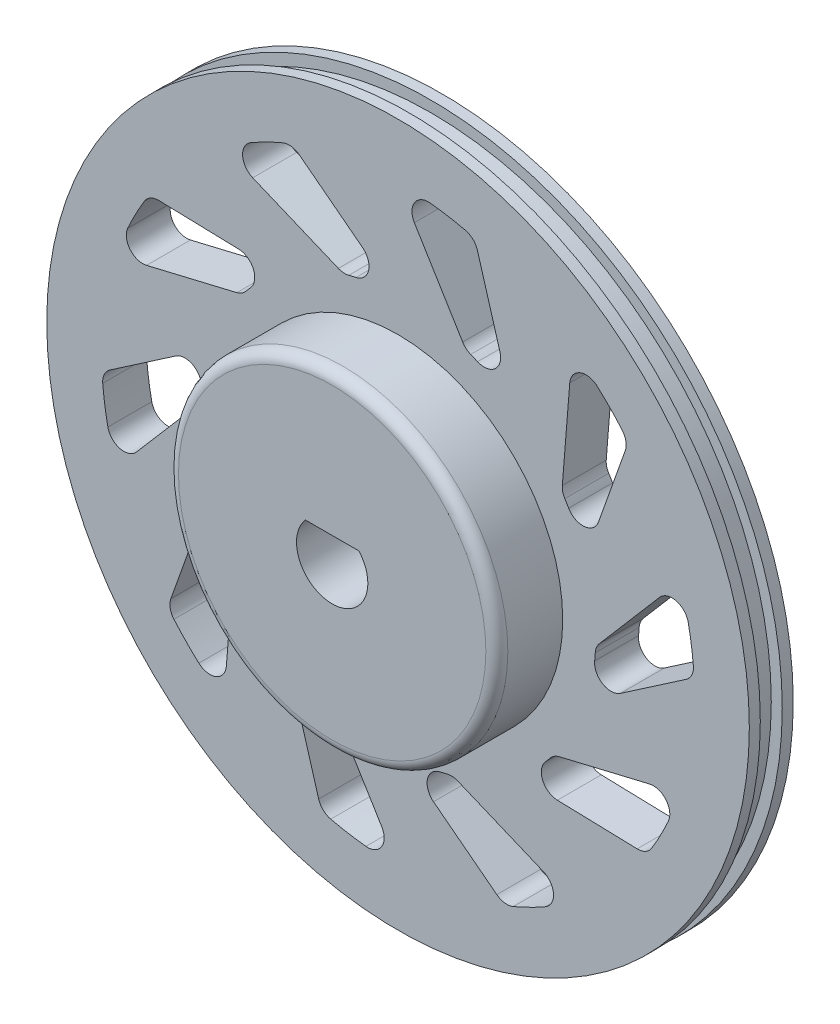
SolidWorks part; units mm, degrees
material "ABS"
ref_plane "Спереди" through (0, 0, 0) normal (0, 0, 1) x (1, 0, 0)
ref_plane "Сверху" through (0, 0, 0) normal (0, 1, 0) x (1, 0, 0)
ref_plane "Справа" through (0, 0, 0) normal (1, 0, 0) x (0, 0, -1)
sketch "Эскиз1" plane through (0, 0, 0) normal (0, 0, 1) x (1, 0, 0)
  circle A0 centre (0, 0) radius 31
  dimension "D1" = 62
extrude "Бобышка-Вытянуть2" add sketch "Эскиз1" along normal blind 2
sketch "Эскиз2" plane through (0, 0, 2) normal (0, 0, 1) x (1, 0, 0)
  circle A0 centre (0, 0) radius 32
  circle A1 centre (0, 0) radius 31 construction
  dimension "D1" = 1
extrude "Бобышка-Вытянуть3" add sketch "Эскиз2" along normal blind 1
sketch "Эскиз3" plane through (0, 0, 0) normal (0, 0, -1) x (-1, 0, 0)
  circle A0 centre (0, 0) radius 32
  circle A1 centre (0, 0) radius 32 construction
extrude "Бобышка-Вытянуть4" add sketch "Эскиз3" along normal blind 1
sketch "Эскиз4" plane through (0, 0, -1) normal (0, 0, -1) x (-1, 0, 0)
  line L0 (2.4372, 2.15) -> (-2.4372, 2.15)
  line L1 (0, -3.25) -> (-5.9785, -3.25) construction
  arc A0 (-2.4372, 2.15) -> (2.4372, 2.15) centre (0, 0) ccw
  dimension "D1" = 6.5
  dimension "D2" = 5.4
sketch "Эскиз6" plane through (0, 0, 3) normal (0, 0, 1) x (1, 0, 0)
  circle A0 centre (0, 0) radius 15
  dimension "D1" = 30
extrude "Бобышка-Вытянуть6" add sketch "Эскиз6" along normal blind 6
extrude "Вырез-Вытянуть4" cut sketch "Эскиз4" against normal through all
sketch "Эскиз7" plane through (0, 0, 3) normal (0, 0, 1) x (1, 0, 0)
  line L0 (0, 0) -> (0, 27) construction
  line L1 (0, 0) -> (9.2345, 25.3717) construction
  line L2 (9.2852, 18.2753) -> (7.2303, 25.2572)
  line L3 (7.2303, 25.2572) -> (6.9881, 26.08) construction
  line L4 (5.8888, 17.3528) -> (1.4844, 24.5682)
  line L5 (1.4844, 24.5682) -> (0, 27) construction
  line L6 (14.9639, 10.5774) -> (15.6417, 19.0035)
  line L7 (18.2539, 9.3273) -> (20.6952, 16.1836)
  line L8 (18.3232, -0.2383) -> (23.8244, 6.1802)
  line L9 (20.2501, -3.1834) -> (26.2553, 0.9285)
  line L10 (14.6838, -10.9629) -> (22.907, -9.0038)
  line L11 (14.5116, -14.4782) -> (21.7867, -14.6813)
  line L12 (5.4356, -17.5001) -> (13.2399, -20.7486)
  line L13 (3.23, -20.2428) -> (8.9964, -24.6833)
  line L14 (-5.8888, -17.3528) -> (-1.4844, -24.5682)
  line L15 (-9.2852, -18.2753) -> (-7.2303, -25.2572)
  line L16 (-14.9639, -10.5774) -> (-15.6417, -19.0035)
  line L17 (-18.2539, -9.3273) -> (-20.6952, -16.1836)
  line L18 (-18.3232, 0.2383) -> (-23.8244, -6.1802)
  line L19 (-20.2501, 3.1834) -> (-26.2553, -0.9285)
  line L20 (-14.6838, 10.9629) -> (-22.907, 9.0038)
  line L21 (-14.5116, 14.4782) -> (-21.7867, 14.6813)
  line L22 (-5.4356, 17.5001) -> (-13.2399, 20.7486)
  line L23 (-3.23, 20.2428) -> (-8.9964, 24.6833)
  circle A0 centre (0, 0) radius 18 construction
  circle A1 centre (0, 0) radius 27 construction
  circle A2 centre (0, 0) radius 32 construction
  circle A3 centre (0, 0) radius 15 construction
  arc A4 (2.9274, 26.8408) -> (6.132, 26.2945) centre (0, 0) cw
  arc A5 (6.6176, 16.7394) -> (7.2427, 16.4786) centre (0, 0) cw
  arc A6 (6.6176, 16.7394) -> (5.8888, 17.3528) centre (7.1691, 18.1343) cw
  arc A7 (6.132, 26.2945) -> (7.2303, 25.2572) centre (5.7913, 24.8337) cw
  arc A8 (7.2427, 16.4786) -> (9.2852, 18.2753) centre (7.8463, 17.8518) ccw
  arc A9 (2.9274, 26.8408) -> (1.4844, 24.5682) centre (2.7648, 25.3497) ccw
  arc A10 (18.145, 19.994) -> (15.6417, 19.0035) centre (17.1369, 18.8832) ccw
  arc A11 (18.145, 19.994) -> (20.4164, 17.6684) centre (0, 0) cw
  arc A12 (20.4164, 17.6684) -> (20.6952, 16.1836) centre (19.2821, 16.6868) cw
  arc A13 (15.1929, 9.6527) -> (15.5453, 9.0743) centre (0, 0) cw
  arc A14 (15.5453, 9.0743) -> (18.2539, 9.3273) centre (16.8408, 9.8305) ccw
  arc A15 (15.1929, 9.6527) -> (14.9639, 10.5774) centre (16.459, 10.4571) cw
  arc A16 (26.4318, 5.5102) -> (23.8244, 6.1802) centre (24.9633, 5.204) ccw
  arc A17 (26.4318, 5.5102) -> (26.9024, 2.2936) centre (0, 0) cw
  arc A18 (26.9024, 2.2936) -> (26.2553, 0.9285) centre (25.4078, 2.1661) cw
  arc A19 (17.9651, -1.121) -> (17.9102, -1.7961) centre (0, 0) cw
  arc A20 (17.9102, -1.7961) -> (20.2501, -3.1834) centre (19.4027, -1.9457) ccw
  arc A21 (17.9651, -1.121) -> (18.3232, -0.2383) centre (19.4621, -1.2144) cw
  arc A22 (24.6225, -11.0784) -> (22.907, -9.0038) centre (23.2546, -10.4629) ccw
  arc A23 (24.6225, -11.0784) -> (23.1126, -13.9573) centre (0, 0) cw
  arc A24 (23.1126, -13.9573) -> (21.7867, -14.6813) centre (21.8286, -13.1819) cw
  arc A25 (13.8751, -11.4665) -> (13.4339, -11.9804) centre (0, 0) cw
  arc A26 (13.4339, -11.9804) -> (14.5116, -14.4782) centre (14.5534, -12.9788) ccw
  arc A27 (13.8751, -11.4665) -> (14.6838, -10.9629) centre (15.0314, -12.4221) cw
  arc A28 (13.4083, -23.4354) -> (13.2399, -20.7486) centre (12.6634, -22.1334) ccw
  arc A29 (13.4083, -23.4354) -> (10.4946, -24.877) centre (0, 0) cw
  arc A30 (10.4946, -24.877) -> (8.9964, -24.6833) centre (9.9116, -23.4949) cw
  arc A31 (4.4854, -17.4322) -> (3.8264, -17.5886) centre (0, 0) cw
  arc A32 (3.8264, -17.5886) -> (3.23, -20.2428) centre (4.1452, -19.0543) ccw
  arc A33 (4.4854, -17.4322) -> (5.4356, -17.5001) centre (4.8592, -18.8849) cw
  arc A34 (-2.9274, -26.8408) -> (-1.4844, -24.5682) centre (-2.7648, -25.3497) ccw
  arc A35 (-2.9274, -26.8408) -> (-6.132, -26.2945) centre (0, 0) cw
  arc A36 (-6.132, -26.2945) -> (-7.2303, -25.2572) centre (-5.7913, -24.8337) cw
  arc A37 (-6.6176, -16.7394) -> (-7.2427, -16.4786) centre (0, 0) cw
  arc A38 (-7.2427, -16.4786) -> (-9.2852, -18.2753) centre (-7.8463, -17.8518) ccw
  arc A39 (-6.6176, -16.7394) -> (-5.8888, -17.3528) centre (-7.1691, -18.1343) cw
  arc A40 (-18.145, -19.994) -> (-15.6417, -19.0035) centre (-17.1369, -18.8832) ccw
  arc A41 (-18.145, -19.994) -> (-20.4164, -17.6684) centre (0, 0) cw
  arc A42 (-20.4164, -17.6684) -> (-20.6952, -16.1836) centre (-19.2821, -16.6868) cw
  arc A43 (-15.1929, -9.6527) -> (-15.5453, -9.0743) centre (0, 0) cw
  arc A44 (-15.5453, -9.0743) -> (-18.2539, -9.3273) centre (-16.8408, -9.8305) ccw
  arc A45 (-15.1929, -9.6527) -> (-14.9639, -10.5774) centre (-16.459, -10.4571) cw
  arc A46 (-26.4318, -5.5102) -> (-23.8244, -6.1802) centre (-24.9633, -5.204) ccw
  arc A47 (-26.4318, -5.5102) -> (-26.9024, -2.2936) centre (0, 0) cw
  arc A48 (-26.9024, -2.2936) -> (-26.2553, -0.9285) centre (-25.4078, -2.1661) cw
  arc A49 (-17.9651, 1.121) -> (-17.9102, 1.7961) centre (0, 0) cw
  arc A50 (-17.9102, 1.7961) -> (-20.2501, 3.1834) centre (-19.4027, 1.9457) ccw
  arc A51 (-17.9651, 1.121) -> (-18.3232, 0.2383) centre (-19.4621, 1.2144) cw
  arc A52 (-24.6225, 11.0784) -> (-22.907, 9.0038) centre (-23.2546, 10.4629) ccw
  arc A53 (-24.6225, 11.0784) -> (-23.1126, 13.9573) centre (0, 0) cw
  arc A54 (-23.1126, 13.9573) -> (-21.7867, 14.6813) centre (-21.8286, 13.1819) cw
  arc A55 (-13.8751, 11.4665) -> (-13.4339, 11.9804) centre (0, 0) cw
  arc A56 (-13.4339, 11.9804) -> (-14.5116, 14.4782) centre (-14.5534, 12.9788) ccw
  arc A57 (-13.8751, 11.4665) -> (-14.6838, 10.9629) centre (-15.0314, 12.4221) cw
  arc A58 (-13.4083, 23.4354) -> (-13.2399, 20.7486) centre (-12.6634, 22.1334) ccw
  arc A59 (-13.4083, 23.4354) -> (-10.4946, 24.877) centre (0, 0) cw
  arc A60 (-10.4946, 24.877) -> (-8.9964, 24.6833) centre (-9.9116, 23.4949) cw
  arc A61 (-4.4854, 17.4322) -> (-3.8264, 17.5886) centre (0, 0) cw
  arc A62 (-3.8264, 17.5886) -> (-3.23, 20.2428) centre (-4.1452, 19.0543) ccw
  arc A63 (-4.4854, 17.4322) -> (-5.4356, 17.5001) centre (-4.8592, 18.8849) cw
  point P16 (6.1564, 16.9145)
  point P22 (10.3244, 14.7447)
  point P136 (0, 0)
  dimension "D1" = 5
  dimension "D2" = 3
  dimension "D5" = 1.5
  dimension "D3" = 15
  dimension "D4" = 15
  dimension "D6" = 20
  dimension "D7" = 10
extrude "Вырез-Вытянуть5" cut sketch "Эскиз7" against normal through all
fillet "Скругление1" radius 1 1 edges at (15, 0, 9)
